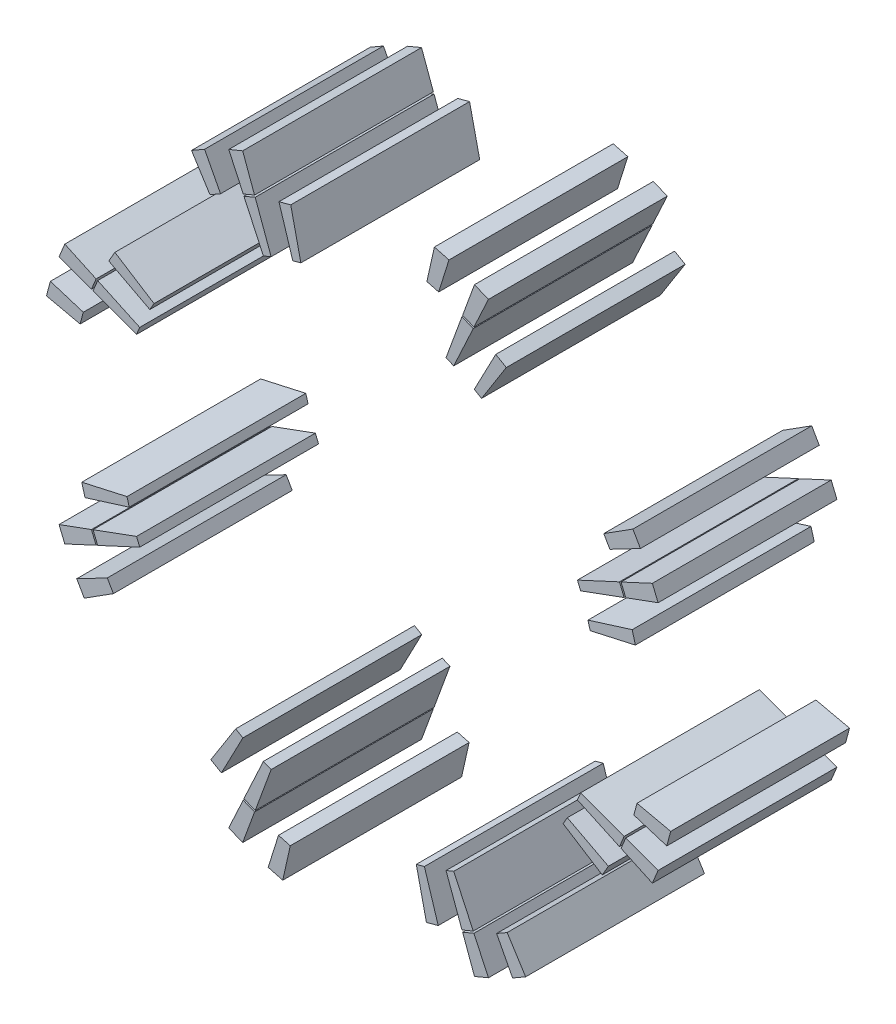
SolidWorks part; units mm, degrees
ref_plane "Спереди" through (0, 0, 0) normal (0, 0, 1) x (1, 0, 0)
ref_plane "Сверху" through (0, 0, 0) normal (0, 1, 0) x (1, 0, 0)
ref_plane "Справа" through (0, 0, 0) normal (1, 0, 0) x (0, 0, -1)
sketch "Эскиз1" plane through (0, 0, 0) normal (0, 0, 1) x (1, 0, 0)
  line L0 (51.7928, 12.9073) -> (61.905, 15.1745)
  line L1 (61.905, 15.1745) -> (61.1985, 17.811)
  line L2 (61.1985, 17.811) -> (51.3076, 14.7184)
  line L3 (51.3076, 14.7184) -> (51.7928, 12.9073)
  line L4 (59.7509, 23.2724) -> (66.9945, 25.9235)
  line L5 (66.9945, 25.9235) -> (65.703, 29.0416)
  line L6 (65.703, 29.0416) -> (58.7063, 25.7942)
  line L7 (58.7063, 25.7942) -> (59.7509, 23.2724)
  line L8 (49.665, 19.5572) -> (59.3947, 23.1249)
  line L9 (59.3947, 23.1249) -> (58.3502, 25.6467)
  line L10 (58.3502, 25.6467) -> (48.9475, 21.2895)
  line L11 (48.9475, 21.2895) -> (49.665, 19.5572)
  line L12 (56.202, 30.8723) -> (63.0377, 34.4463)
  line L13 (63.0377, 34.4463) -> (61.3502, 37.3691)
  line L14 (61.3502, 37.3691) -> (54.8372, 33.2362)
  line L15 (54.8372, 33.2362) -> (56.202, 30.8723)
  line L16 (27.4962, 45.7499) -> (33.0435, 54.5034)
  line L17 (33.0435, 54.5034) -> (30.6796, 55.8682)
  line L18 (30.6796, 55.8682) -> (25.8724, 46.6874)
  line L19 (25.8724, 46.6874) -> (27.4962, 45.7499)
  line L20 (25.7942, 58.7063) -> (29.0416, 65.703)
  line L21 (29.0416, 65.703) -> (25.9235, 66.9945)
  line L22 (25.9235, 66.9945) -> (23.2724, 59.7509)
  line L23 (23.2724, 59.7509) -> (25.7942, 58.7063)
  line L24 (21.2895, 48.9475) -> (25.6467, 58.3502)
  line L25 (25.6467, 58.3502) -> (23.1249, 59.3947)
  line L26 (23.1249, 59.3947) -> (19.5572, 49.665)
  line L27 (19.5572, 49.665) -> (21.2895, 48.9475)
  line L28 (17.9108, 61.5709) -> (20.2172, 68.9316)
  line L29 (20.2172, 68.9316) -> (16.9572, 69.8051)
  line L30 (16.9572, 69.8051) -> (15.2742, 62.2773)
  line L31 (15.2742, 62.2773) -> (17.9108, 61.5709)
  line L32 (-12.9073, 51.7928) -> (-15.1745, 61.905)
  line L33 (-15.1745, 61.905) -> (-17.811, 61.1985)
  line L34 (-17.811, 61.1985) -> (-14.7184, 51.3076)
  line L35 (-14.7184, 51.3076) -> (-12.9073, 51.7928)
  line L36 (-23.2724, 59.7509) -> (-25.9235, 66.9945)
  line L37 (-25.9235, 66.9945) -> (-29.0416, 65.703)
  line L38 (-29.0416, 65.703) -> (-25.7942, 58.7063)
  line L39 (-25.7942, 58.7063) -> (-23.2724, 59.7509)
  line L40 (-19.5572, 49.665) -> (-23.1249, 59.3947)
  line L41 (-23.1249, 59.3947) -> (-25.6467, 58.3502)
  line L42 (-25.6467, 58.3502) -> (-21.2895, 48.9475)
  line L43 (-21.2895, 48.9475) -> (-19.5572, 49.665)
  line L44 (-30.8723, 56.202) -> (-34.4463, 63.0377)
  line L45 (-34.4463, 63.0377) -> (-37.3691, 61.3502)
  line L46 (-37.3691, 61.3502) -> (-33.2362, 54.8372)
  line L47 (-33.2362, 54.8372) -> (-30.8723, 56.202)
  line L48 (-45.7499, 27.4962) -> (-54.5034, 33.0435)
  line L49 (-54.5034, 33.0435) -> (-55.8682, 30.6796)
  line L50 (-55.8682, 30.6796) -> (-46.6874, 25.8724)
  line L51 (-46.6874, 25.8724) -> (-45.7499, 27.4962)
  line L52 (-58.7063, 25.7942) -> (-65.703, 29.0416)
  line L53 (-65.703, 29.0416) -> (-66.9945, 25.9235)
  line L54 (-66.9945, 25.9235) -> (-59.7509, 23.2724)
  line L55 (-59.7509, 23.2724) -> (-58.7063, 25.7942)
  line L56 (-48.9475, 21.2895) -> (-58.3502, 25.6467)
  line L57 (-58.3502, 25.6467) -> (-59.3947, 23.1249)
  line L58 (-59.3947, 23.1249) -> (-49.665, 19.5572)
  line L59 (-49.665, 19.5572) -> (-48.9475, 21.2895)
  line L60 (-61.5709, 17.9108) -> (-68.9316, 20.2172)
  line L61 (-68.9316, 20.2172) -> (-69.8051, 16.9572)
  line L62 (-69.8051, 16.9572) -> (-62.2773, 15.2742)
  line L63 (-62.2773, 15.2742) -> (-61.5709, 17.9108)
  line L64 (-51.7928, -12.9073) -> (-61.905, -15.1745)
  line L65 (-61.905, -15.1745) -> (-61.1985, -17.811)
  line L66 (-61.1985, -17.811) -> (-51.3076, -14.7184)
  line L67 (-51.3076, -14.7184) -> (-51.7928, -12.9073)
  line L68 (-59.7509, -23.2724) -> (-66.9945, -25.9235)
  line L69 (-66.9945, -25.9235) -> (-65.703, -29.0416)
  line L70 (-65.703, -29.0416) -> (-58.7063, -25.7942)
  line L71 (-58.7063, -25.7942) -> (-59.7509, -23.2724)
  line L72 (-49.665, -19.5572) -> (-59.3947, -23.1249)
  line L73 (-59.3947, -23.1249) -> (-58.3502, -25.6467)
  line L74 (-58.3502, -25.6467) -> (-48.9475, -21.2895)
  line L75 (-48.9475, -21.2895) -> (-49.665, -19.5572)
  line L76 (-56.202, -30.8723) -> (-63.0377, -34.4463)
  line L77 (-63.0377, -34.4463) -> (-61.3502, -37.3691)
  line L78 (-61.3502, -37.3691) -> (-54.8372, -33.2362)
  line L79 (-54.8372, -33.2362) -> (-56.202, -30.8723)
  line L80 (-27.4962, -45.7499) -> (-33.0435, -54.5034)
  line L81 (-33.0435, -54.5034) -> (-30.6796, -55.8682)
  line L82 (-30.6796, -55.8682) -> (-25.8724, -46.6874)
  line L83 (-25.8724, -46.6874) -> (-27.4962, -45.7499)
  line L84 (-25.7942, -58.7063) -> (-29.0416, -65.703)
  line L85 (-29.0416, -65.703) -> (-25.9235, -66.9945)
  line L86 (-25.9235, -66.9945) -> (-23.2724, -59.7509)
  line L87 (-23.2724, -59.7509) -> (-25.7942, -58.7063)
  line L88 (-21.2895, -48.9475) -> (-25.6467, -58.3502)
  line L89 (-25.6467, -58.3502) -> (-23.1249, -59.3947)
  line L90 (-23.1249, -59.3947) -> (-19.5572, -49.665)
  line L91 (-19.5572, -49.665) -> (-21.2895, -48.9475)
  line L92 (-17.9108, -61.5709) -> (-20.2172, -68.9316)
  line L93 (-20.2172, -68.9316) -> (-16.9572, -69.8051)
  line L94 (-16.9572, -69.8051) -> (-15.2742, -62.2773)
  line L95 (-15.2742, -62.2773) -> (-17.9108, -61.5709)
  line L96 (12.9073, -51.7928) -> (15.1745, -61.905)
  line L97 (15.1745, -61.905) -> (17.811, -61.1985)
  line L98 (17.811, -61.1985) -> (14.7184, -51.3076)
  line L99 (14.7184, -51.3076) -> (12.9073, -51.7928)
  line L100 (23.2724, -59.7509) -> (25.9235, -66.9945)
  line L101 (25.9235, -66.9945) -> (29.0416, -65.703)
  line L102 (29.0416, -65.703) -> (25.7942, -58.7063)
  line L103 (25.7942, -58.7063) -> (23.2724, -59.7509)
  line L104 (19.5572, -49.665) -> (23.1249, -59.3947)
  line L105 (23.1249, -59.3947) -> (25.6467, -58.3502)
  line L106 (25.6467, -58.3502) -> (21.2895, -48.9475)
  line L107 (21.2895, -48.9475) -> (19.5572, -49.665)
  line L108 (30.8723, -56.202) -> (34.4463, -63.0377)
  line L109 (34.4463, -63.0377) -> (37.3691, -61.3502)
  line L110 (37.3691, -61.3502) -> (33.2362, -54.8372)
  line L111 (33.2362, -54.8372) -> (30.8723, -56.202)
  line L112 (45.7499, -27.4962) -> (54.5034, -33.0435)
  line L113 (54.5034, -33.0435) -> (55.8682, -30.6796)
  line L114 (55.8682, -30.6796) -> (46.6874, -25.8724)
  line L115 (46.6874, -25.8724) -> (45.7499, -27.4962)
  line L116 (58.7063, -25.7942) -> (65.703, -29.0416)
  line L117 (65.703, -29.0416) -> (66.9945, -25.9235)
  line L118 (66.9945, -25.9235) -> (59.7509, -23.2724)
  line L119 (59.7509, -23.2724) -> (58.7063, -25.7942)
  line L120 (48.9475, -21.2895) -> (58.3502, -25.6467)
  line L121 (58.3502, -25.6467) -> (59.3947, -23.1249)
  line L122 (59.3947, -23.1249) -> (49.665, -19.5572)
  line L123 (49.665, -19.5572) -> (48.9475, -21.2895)
  line L124 (61.5709, -17.9108) -> (68.9316, -20.2172)
  line L125 (68.9316, -20.2172) -> (69.8051, -16.9572)
  line L126 (69.8051, -16.9572) -> (62.2773, -15.2742)
  line L127 (62.2773, -15.2742) -> (61.5709, -17.9108)
extrude "Slot_copper_envelopes" add sketch "Эскиз1" along normal blind 40 from offset 20 separate body
